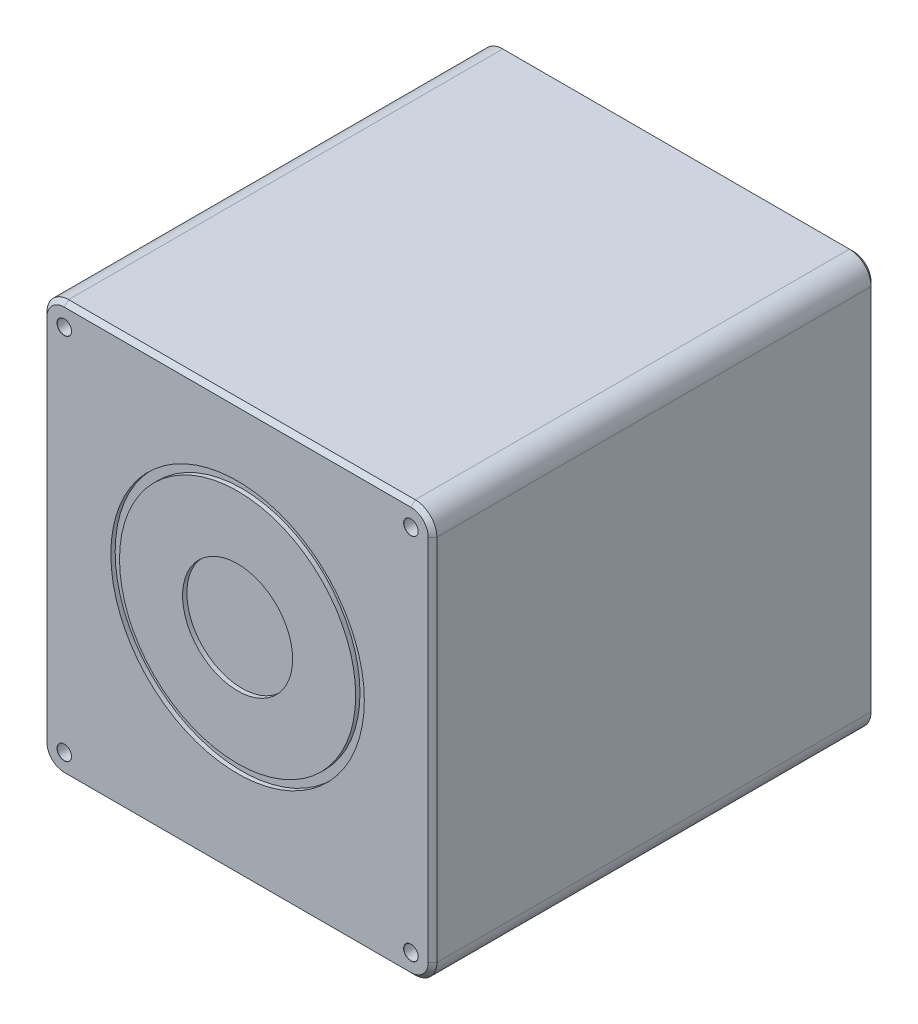
SolidWorks part; units mm, degrees
ref_plane "Front Plane" through (0, 0, 0) normal (0, 0, 1) x (1, 0, 0)
ref_plane "Top Plane" through (0, 0, 0) normal (0, 1, 0) x (1, 0, 0)
ref_plane "Right Plane" through (0, 0, 0) normal (1, 0, 0) x (0, 0, -1)
sketch "Sketch1" plane through (0, 0, 0) normal (0, 0, 1) x (1, 0, 0)
  line L1 (-45, 47.5) -> (45, 47.5)
  line L2 (-45, 47.5) -> (-45, -47.5)
  line L3 (-45, -47.5) -> (45, -47.5)
  line L4 (45, 47.5) -> (45, -47.5)
  line L5 (-45, 47.5) -> (45, -47.5) construction
  line L6 (-45, -47.5) -> (45, 47.5) construction
  point P0 (0, 0)
  dimension "D1" = 90
  dimension "D2" = 95
extrude "Boss-Extrude1" add sketch "Sketch1" against normal blind 102.2
sketch "Sketch2" plane through (0, 0, 0) normal (0, 0, 1) x (1, 0, 0)
  line L0 (-45, 2.5) -> (45, 2.5) construction
  line L1 (-45, 47.5) -> (-45, -47.5) construction
  line L2 (45, -47.5) -> (45, 47.5) construction
  line L3 (-45, -47.5) -> (45, -47.5) construction
  circle A0 centre (0, 2.5) radius 29.25
  point P10 (0, 2.5)
  dimension "D1" = 58.5
  dimension "D2" = 50
extrude "Cut-Extrude1" cut sketch "Sketch2" against normal blind 1
sketch "Sketch3" plane through (0, 0, -1) normal (0, 0, 1) x (1, 0, 0)
  circle A0 centre (0, 2.5) radius 27.25
  circle A1 centre (0, 2.5) radius 29.25 construction
  dimension "D1" = 54.5
extrude "Boss-Extrude2" add sketch "Sketch3" along normal blind 1
sketch "Sketch4" plane through (0, 0, 0) normal (0, 0, 1) x (1, 0, 0)
  line L0 (0, 2.5) -> (0, 42.5) construction
  line L1 (-40, 42.5) -> (40, 42.5) construction
  line L2 (0, 2.5) -> (0, -42.5) construction
  line L3 (-40, -42.5) -> (40, -42.5) construction
  circle A0 centre (0, 2.5) radius 27.25 construction
  point P5 (0, 42.5)
  point P10 (0, -42.5)
  dimension "D1" = 40
  dimension "D2" = 80
  dimension "D3" = 45
  dimension "D4" = 80
hole_wizard "Tap Drill for M4 Tap1" positions "Sketch5" profile "Sketch6" hole size "M4" standard "ISO"
sketch "Sketch5" plane through (0, 0, 0) normal (0, 0, 1) x (1, 0, 0)
  point P0 (-40, 42.5)
  point P3 (40, 42.5)
  point P6 (-40, -42.5)
  point P9 (40, -42.5)
sketch "Sketch6" plane through (-40, 42.5, 0) normal (1, 0, 0) x (0, -1, 0)
  line L0 (0, 0) -> (0, 5.9914)
  line L1 (0, 5.9914) -> (1.65, 5)
  line L2 (1.65, 5) -> (1.65, 0.025)
  line L3 (1.65, 0.025) -> (1.675, 0)
  line L5 (1.675, 0) -> (0, 0)
  line L6 (-1.65, 0.025) -> (-1.675, 0) construction
  line L10 (0, 5.9914) -> (-1.65, 5) construction
  line L11 (0, -6.35) -> (0, 107.95) construction
  dimension "Hole Dia." = 3.3
  dimension "Hole Depth" = 5
  dimension "Near C'Sink Dia." = 3.35
  dimension "Near C'Sink Angle" = 90
  dimension "Drill Angle" = 118
sketch "Sketch7" plane through (0, -47.5, 0) normal (0, -1, 0) x (-1, 0, 0)
  line L0 (-30, 83.9) -> (30, 83.9) construction
  line L1 (0, 102.2) -> (0, 83.9) construction
  line L2 (45, 102.2) -> (-45, 102.2) construction
  point P6 (0, 83.9)
  dimension "D1" = 18.3
  dimension "D2" = 60
hole_wizard "Tap Drill for M4 Tap2" positions "Sketch8" profile "Sketch9" hole size "M4" standard "ISO"
sketch "Sketch8" plane through (0, -47.5, 0) normal (0, -1, 0) x (-1, 0, 0)
  point P0 (-30, 83.9)
  point P3 (30, 83.9)
sketch "Sketch9" plane through (30, -47.5, -83.9) normal (1, 0, 0) x (0, 0, -1)
  line L0 (0, 0) -> (0, 5.9914)
  line L1 (0, 5.9914) -> (1.65, 5)
  line L2 (1.65, 5) -> (1.65, 0.025)
  line L3 (1.65, 0.025) -> (1.675, 0)
  line L5 (1.675, 0) -> (0, 0)
  line L6 (-1.65, 0.025) -> (-1.675, 0) construction
  line L10 (0, 5.9914) -> (-1.65, 5) construction
  line L11 (0, -6.35) -> (0, 107.95) construction
  dimension "Hole Dia." = 3.3
  dimension "Hole Depth" = 5
  dimension "Near C'Sink Dia." = 3.35
  dimension "Near C'Sink Angle" = 90
  dimension "Drill Angle" = 118
sketch "Sketch10" plane through (0, -47.5, 0) normal (0, -1, 0) x (-1, 0, 0)
  line L0 (0, 102.2) -> (0, 48.9) construction
  line L1 (45, 102.2) -> (-45, 102.2) construction
  dimension "D1" = 53.3
hole_wizard "Tap Drill for 1/4-20 Tap1" positions "Sketch11" profile "Sketch12" hole size "1/4-20" standard "ANSI Inch"
sketch "Sketch11" plane through (0, -47.5, 0) normal (0, -1, 0) x (-1, 0, 0)
  point P0 (0, 48.9)
sketch "Sketch12" plane through (0, -47.5, -48.9) normal (1, 0, 0) x (0, 0, -1)
  line L0 (0, 0) -> (0, 6.5338)
  line L1 (0, 6.5338) -> (2.5527, 5)
  line L2 (2.5527, 5) -> (2.5527, 0.635)
  line L3 (2.5527, 0.635) -> (3.1877, 0)
  line L5 (3.1877, 0) -> (0, 0)
  line L6 (-2.5527, 0.635) -> (-3.1877, 0) construction
  line L10 (0, 6.5338) -> (-2.5527, 5) construction
  line L11 (0, -6.35) -> (0, 107.95) construction
  dimension "Hole Dia." = 5.1054
  dimension "Hole Depth" = 5
  dimension "Near C'Sink Dia." = 6.3754
  dimension "Near C'Sink Angle" = 90
  dimension "Drill Angle" = 118
fillet "Fillet1" radius 5 4 edges at (45, -47.5, -51.1) (-45, -47.5, -51.1) (-45, 47.5, -51.1) (45, 47.5, -51.1)
chamfer "Chamfer1" distance 1 angle 45 16 edges at (0, -47.5, -102.2) (43.5355, -46.0355, -102.2) (-43.5355, -46.0355, -102.2) (45, 0, -102.2) (-45, 0, -102.2) (43.5355, 46.0355, -102.2) (-43.5355, 46.0355, -102.2) (0, 47.5, -102.2) (0, -47.5, 0) (43.5355, -46.0355, 0) (-43.5355, -46.0355, 0) (45, 0, 0) (-45, 0, 0) (43.5355, 46.0355, 0) (-43.5355, 46.0355, 0) (0, 47.5, 0)
sketch "Sketch13" plane through (0, 0, 0) normal (0, 0, 1) x (1, 0, 0)
  circle A0 centre (0, 2.5) radius 12.7
  circle A1 centre (0, 2.5) radius 27.25 construction
  dimension "D1" = 25.4
extrude "Cut-Extrude2" cut sketch "Sketch13" against normal blind 1
